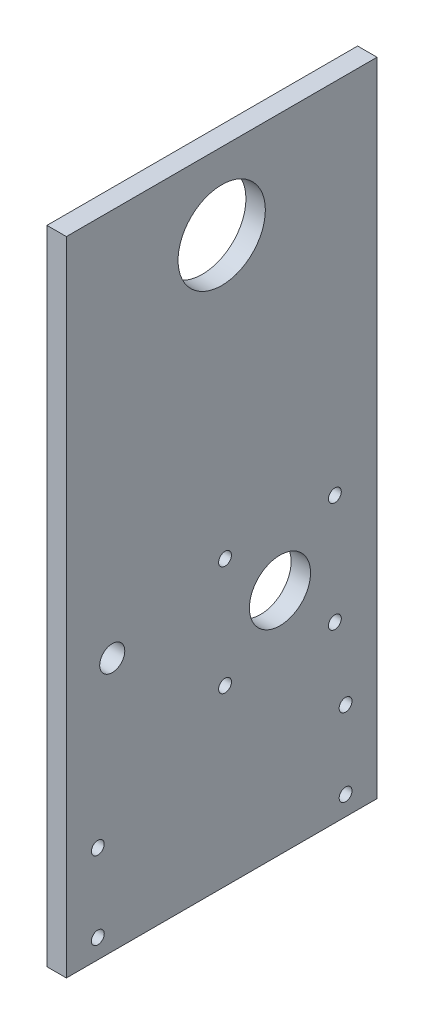
SolidWorks part; units mm, degrees
ref_plane "Plan de face" through (0, 0, 0) normal (0, 0, 1) x (1, 0, 0)
ref_plane "Plan de dessus" through (0, 0, 0) normal (0, 1, 0) x (1, 0, 0)
ref_plane "Plan de droite" through (0, 0, 0) normal (1, 0, 0) x (0, 0, -1)
sketch "Sketch1" plane through (0, 0, 0) normal (1, 0, 0) x (0, 0, -1)
  line L0 (-50.8, -66.9) -> (50.8, -66.9) construction
  line L1 (-50.8, 105) -> (50.8, 105)
  line L2 (-50.8, 105) -> (-50.8, -105)
  line L3 (-50.8, -105) -> (50.8, -105)
  line L4 (50.8, 105) -> (50.8, -105)
  line L5 (-50.8, 105) -> (50.8, -105) construction
  line L6 (-50.8, -105) -> (50.8, 105) construction
  line L7 (1.0895, -48.1105) -> (37.0105, -12.1895) construction
  line L8 (1.0895, -12.1895) -> (37.0105, -48.1105) construction
  line L9 (0, -66.9) -> (0, -105) construction
  line L11 (-40.513, -98.65) -> (40.513, -98.65) construction
  line L12 (-40.513, -98.65) -> (-40.513, -73.25) construction
  line L13 (-40.513, -73.25) -> (40.513, -73.25) construction
  line L14 (40.513, -98.65) -> (40.513, -73.25) construction
  circle A0 centre (-40.513, -98.65) radius 2.1
  circle A1 centre (40.513, -98.65) radius 2.1
  circle A2 centre (19.05, -30.15) radius 31.75 construction
  circle A3 centre (19.05, -30.15) radius 10
  circle A4 centre (19.05, -30.15) radius 25.4 construction
  circle A5 centre (37.0105, -12.1895) radius 2.1
  circle A6 centre (1.0895, -48.1105) radius 2.1
  circle A7 centre (1.0895, -12.1895) radius 2.1
  circle A8 centre (37.0105, -48.1105) radius 2.1
  circle A9 centre (-35.8, -21.9) radius 4.1
  circle A10 centre (0, 80) radius 14.275
  circle A11 centre (-35.8, -21.9) radius 41 construction
  circle A12 centre (0, 80) radius 81.5 construction
  circle A13 centre (-40.513, -73.25) radius 2.1
  circle A14 centre (40.513, -73.25) radius 2.1
  point P0 (0, 0)
  dimension "D3" = 4.2
  dimension "D4" = 4.2
  dimension "D10" = 63.5
  dimension "D13" = 20
  dimension "D14" = 50.8
  dimension "D16" = 4.2
  dimension "D17" = 4.2
  dimension "D19" = 4.2
  dimension "D20" = 4.2
  dimension "D21" = 8.2
  dimension "D24" = 28.55
  dimension "D27" = 82
  dimension "D28" = 163
  dimension "D29" = 4.2
  dimension "D30" = 4.2
  dimension "D1" = 210
  dimension "D2" = 101.6
  dimension "D9" = 38.1
  dimension "D11" = 31.75
  dimension "D12" = 36.75
  dimension "D15" = 45
  dimension "D18" = 90
  dimension "D22" = 15
  dimension "D23" = 45
  dimension "D25" = 25
  dimension "D26" = 50.8
  dimension "D5" = 40.513
  dimension "D6" = 40.513
  dimension "D7" = 6.35
  dimension "D8" = 6.35
extrude "Boss-Extrude1" add sketch "Sketch1" along normal blind 6.35
equation "\"D11@Sketch1\"=\"D10@Sketch1\"/2"
equation "\"D12@Sketch1\"=\"D10@Sketch1\"/2+5"
equation "\"D26@Sketch1\"=\"D2@Sketch1\"/2"
equation "\"D6@Sketch1\"=3.19in/2"
equation "\"D5@Sketch1\"=\"D6@Sketch1\""
equation "\"D7@Sketch1\"=0.25in"
equation "\"D4@Sketch1\"=\"D3@Sketch1\""
equation "\"D29@Sketch1\"=\"D3@Sketch1\""
equation "\"D30@Sketch1\"=\"D3@Sketch1\""
